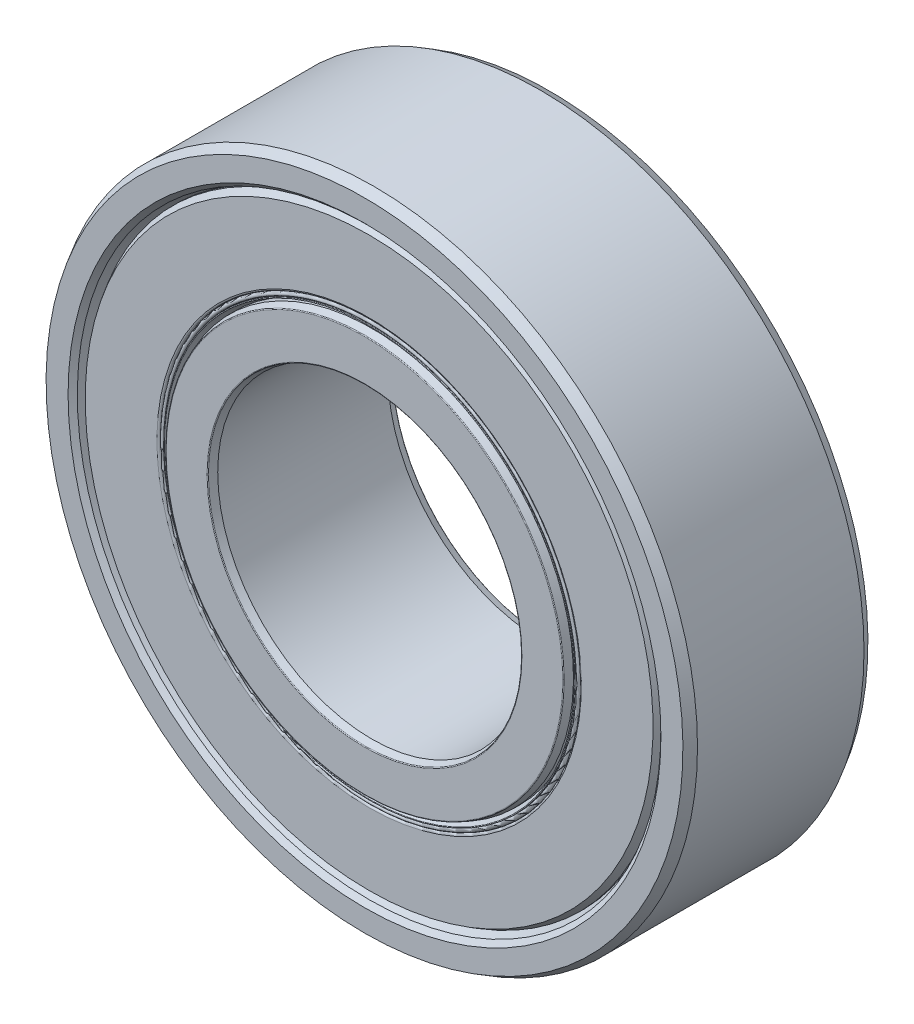
SolidWorks part; units mm, degrees
ref_plane "Front Plane" through (0, 0, 0) normal (0, 0, 1) x (1, 0, 0)
ref_plane "Top Plane" through (0, 0, 0) normal (0, 1, 0) x (1, 0, 0)
ref_plane "Right Plane" through (0, 0, 0) normal (1, 0, 0) x (0, 0, -1)
sketch "Sketch1" plane through (0, 0, 0) normal (0, 0, 1) x (1, 0, 0)
  line L0 (-21, 0) -> (21, 0) construction
  line L1 (-10, 0) -> (10, 0) construction
  circle A0 centre (0, 0) radius 10 construction
  circle A1 centre (0, 0) radius 21 construction
  point P3 (0, 0)
  point P6 (0, 0)
  point P7 (0, -10)
  point P11 (0, -21)
  point P12 (0, 10)
  point P13 (0, 21)
  dimension "OD" = 42
  dimension "ID" = 20
sketch "Sketch2" plane through (0, 0, 0) normal (1, 0, 0) x (0, 0, -1)
  line L0 (-6, 21) -> (6, 21) construction
  line L1 (0, 21) -> (0, -21) construction
  line L2 (5.4, 21) -> (-5.4, 21)
  line L3 (-5.4, 21) -> (-6, 20.6536)
  line L4 (-6, 20.6536) -> (-6, 19.227)
  line L5 (-5.049, 18.69) -> (-2.796, 18.69)
  line L6 (5.049, 18.69) -> (2.796, 18.69)
  line L7 (6, 20.6536) -> (6, 19.227)
  line L8 (5.4, 21) -> (6, 20.6536)
  line L9 (-2.796, 18.69) -> (-2.796, 21) construction
  line L10 (-2.796, 19.845) -> (0, 19.845) construction
  line L11 (0, 21) -> (0, -21) construction
  line L12 (-6, 0) -> (6, 0) construction
  line L13 (6, 10) -> (-6, 10) construction
  line L14 (-6, 10) -> (-6, -10) construction
  line L15 (-6, -10) -> (6, -10) construction
  line L16 (6, 21) -> (6, -21) construction
  line L20 (-5.049, 18.69) -> (-5.7, 18.927)
  line L21 (-5.7, 18.927) -> (-6, 19.227)
  line L26 (5.7, 18.927) -> (6, 19.227)
  line L27 (5.049, 18.69) -> (5.7, 18.927)
  arc A0 (-2.796, 18.69) -> (2.796, 18.69) centre (0, 15.8833) cw
  circle A1 centre (0, 15.8833) radius 3.9617 construction
  point P17 (0, 0)
  point P21 (0, 21)
  point P30 (0, -10)
  dimension "Width" = 12
  dimension "D3" = 5.592
  dimension "For Shaft Diameter" = 20
  dimension "For Housing ID" = 42
  dimension "D4" = 37.38
  dimension "D2" = 20
  dimension "D5" = 45
  dimension "D1" = 30
  dimension "D6" = 0.6
  dimension "D7" = 0.3
sketch "Sketch3" plane through (0, 0, 0) normal (1, 0, 0) x (0, 0, -1)
  line L14 (-5.049, 18.69) -> (-5.7, 18.927) construction
  line L15 (-5.7, 18.927) -> (-6, 19.227) construction
  line L16 (-6, 20.6536) -> (-6, 19.227) construction
  line L17 (-5.4, 21) -> (-6, 20.6536) construction
  line L18 (5.4, 21) -> (-5.4, 21) construction
  line L19 (5.4, 21) -> (6, 20.6536) construction
  line L20 (6, 20.6536) -> (6, 19.227) construction
  line L21 (5.7, 18.927) -> (6, 19.227) construction
  line L22 (5.049, 18.69) -> (5.7, 18.927) construction
  line L23 (5.049, 18.69) -> (2.796, 18.69) construction
  line L24 (-5.049, 18.69) -> (-2.796, 18.69) construction
  line L25 (-5.049, 18.69) -> (-5.7, 18.927)
  line L26 (-5.7, 18.927) -> (-6, 19.227)
  line L27 (-6, 20.6536) -> (-6, 19.227)
  line L28 (-5.4, 21) -> (-6, 20.6536)
  line L29 (5.4, 21) -> (-5.4, 21)
  line L30 (5.4, 21) -> (6, 20.6536)
  line L31 (6, 20.6536) -> (6, 19.227)
  line L32 (5.7, 18.927) -> (6, 19.227)
  line L33 (5.049, 18.69) -> (5.7, 18.927)
  line L34 (5.049, 18.69) -> (2.796, 18.69)
  line L35 (-5.049, 18.69) -> (-2.796, 18.69)
  arc A2 (2.796, 18.69) -> (-2.796, 18.69) centre (0, 15.8833) ccw construction
  arc A3 (2.796, 18.69) -> (-2.796, 18.69) centre (0, 15.8833) ccw
revolve "Revolve1" add sketch "Sketch3" angle 360 about L12
sketch "Sketch4" plane through (0, 0, 0) normal (1, 0, 0) x (0, 0, -1)
  line L0 (0, 21) -> (0, -21) construction
  line L1 (0, 21) -> (0, -21) construction
  line L2 (-5.52, 10) -> (-5.9605, 10.1603)
  line L3 (-6, 10.2167) -> (-6, 12.8598)
  line L4 (5.52, 13.0765) -> (5.9605, 12.9162)
  line L5 (-5.52, 13.0765) -> (-2.796, 13.0765)
  line L6 (-5.52, 10) -> (5.52, 10)
  line L7 (6, 20.6536) -> (6, 19.227) construction
  line L8 (5.52, 10) -> (5.9605, 10.1603)
  line L9 (2.796, 13.0765) -> (2.796, 10) construction
  line L10 (6, 10.2167) -> (6, 12.8598)
  line L11 (5.52, 13.0765) -> (2.796, 13.0765)
  line L12 (-5.52, 13.0765) -> (-5.9605, 12.9162)
  line L14 (2.796, 11.5383) -> (6, 11.5383) construction
  circle A0 centre (0, 15.8833) radius 3.9617 construction
  arc A1 (2.796, 13.0765) -> (-2.796, 13.0765) centre (0, 15.8833) cw
  arc A2 (5.9605, 12.9162) -> (6, 12.8598) centre (5.94, 12.8598) cw
  arc A3 (-5.9605, 12.9162) -> (-6, 12.8598) centre (-5.94, 12.8598) ccw
  arc A4 (5.9605, 10.1603) -> (6, 10.2167) centre (5.94, 10.2167) ccw
  arc A5 (-5.9605, 10.1603) -> (-6, 10.2167) centre (-5.94, 10.2167) cw
  point P14 (6, 10.1747)
  dimension "D2" = 0.06
  dimension "D1" = 20
  dimension "D3" = 0.48
revolve "Revolve2" add sketch "Sketch4" angle 360 about L12
sketch "Sketch5" plane through (0, 0, 0) normal (1, 0, 0) x (0, 0, -1)
  line L0 (-3.9617, 15.8833) -> (3.9617, 15.8833)
  arc A2 (-3.9617, 15.8833) -> (3.9617, 15.8833) centre (0, 15.8833) cw
  arc A3 (2.796, 18.69) -> (-2.796, 18.69) centre (0, 15.8833) ccw construction
revolve "Revolve3" add sketch "Sketch5" angle 360 about L0
pattern_circular "CirPattern1" count 9 over 360 about axis through (0, 0, 0) along (0, 0, 1) of bodies 104
sketch "Sketch6" plane through (0, 0, 0) normal (1, 0, 0) x (0, 0, -1)
  line L1 (-5.2237, 18.69) -> (-3.9617, 18.69)
  line L2 (-5.7, 18.415) -> (-5.7, 13.764)
  line L3 (-5.5625, 13.6265) -> (-3.9617, 13.6265)
  line L4 (-3.9617, 18.69) -> (-3.9617, 13.6265)
  line L6 (-5.4, 21) -> (-6, 20.6536) construction
  line L7 (0, 21) -> (0, 10) construction
  line L8 (5.5625, 13.6265) -> (3.9617, 13.6265)
  line L9 (3.9617, 18.69) -> (3.9617, 13.6265)
  line L10 (5.2237, 18.69) -> (3.9617, 18.69)
  line L11 (5.7, 18.415) -> (5.7, 13.764)
  line L13 (-5.52, 13.0765) -> (-2.796, 13.0765) construction
  line L14 (-5.7, 18.415) -> (-5.2237, 18.69)
  line L15 (-5.049, 18.69) -> (-2.796, 18.69) construction
  line L16 (5.7, 18.415) -> (5.2237, 18.69)
  arc A0 (-5.7, 13.764) -> (-5.5625, 13.6265) centre (-5.5625, 13.764) ccw
  circle A1 centre (0, 15.8833) radius 3.9617 construction
  arc A2 (5.7, 13.764) -> (5.5625, 13.6265) centre (5.5625, 13.764) cw
  point P10 (-5.7, 20.8268)
  point P26 (-5.7, 13.6265)
  dimension "D3" = 0.1375
  dimension "D1" = 0.55
  dimension "D2" = 0.275
revolve "Revolve4" add sketch "Sketch6" angle 360 about L12
sketch "Sketch7" plane through (0, 0, 0) normal (1, 0, 0) x (0, 0, -1)
  line L0 (-3.9617, 13.0765) -> (-5.0846, 13.0765)
  line L5 (-5.0846, 13.0765) -> (-5.6803, 13.2933)
  line L6 (-5.67, 13.3515) -> (-5.5625, 13.3515)
  line L7 (0, 11.9215) -> (0, 10) construction
  line L8 (0, 21) -> (0, -21) construction
  line L9 (-5.5625, 13.6265) -> (-3.9617, 13.6265)
  line L12 (-3.9617, 13.6265) -> (-3.9617, 13.0765)
  line L13 (-5.52, 13.0765) -> (-2.796, 13.0765) construction
  line L14 (-5.5625, 13.6265) -> (-3.9617, 13.6265) construction
  line L15 (-3.9617, 18.69) -> (-3.9617, 13.6265) construction
  line L16 (3.9617, 13.6265) -> (3.9617, 13.0765)
  line L17 (5.5625, 13.6265) -> (3.9617, 13.6265)
  line L18 (5.67, 13.3515) -> (5.5625, 13.3515)
  line L19 (5.0846, 13.0765) -> (5.6803, 13.2933)
  line L20 (3.9617, 13.0765) -> (5.0846, 13.0765)
  circle A2 centre (0, 15.8833) radius 3.9617 construction
  arc A5 (-5.6803, 13.2933) -> (-5.67, 13.3515) centre (-5.67, 13.3215) cw
  arc A6 (-5.5625, 13.3515) -> (-5.5625, 13.6265) centre (-5.5625, 13.489) cw
  arc A7 (5.5625, 13.3515) -> (5.5625, 13.6265) centre (5.5625, 13.489) ccw
  arc A8 (5.6803, 13.2933) -> (5.67, 13.3515) centre (5.67, 13.3215) ccw
  point P14 (-5.7, 13.489)
  point P27 (-3.9617, 13.3515)
  point P36 (-5.7, 13.3215)
  dimension "D1" = 20
  dimension "D2" = 0.03
revolve "Revolve5" add sketch "Sketch7" angle 360 about L12
equation "\"D3@Sketch2\"=\"Width@Sketch2\" *.466"
equation "\"D4@Sketch2\"=\"OD@Sketch1\"*.89"
equation "\"D1@Sketch6\"=(\"OD@Sketch1\"-\"ID@Sketch1\")*.025"
equation "\"D2@Sketch6\"=\"D1@Sketch6\"*.5"
equation "\"D3@Sketch6\"=\"D1@Sketch6\"*.25"
equation "\"D3@Sketch4\"=\"Width@Sketch2\"*.04"
equation "\"D2@Sketch4\"=\"D3@Sketch4\"*.125"
equation "\"D6@Sketch2\"=\"Width@Sketch2\"*.05"
equation "\"D7@Sketch2\"=\"D6@Sketch2\"*.5"
equation "\"D2@Sketch7\"=\"D6@Sketch2\"*.05"
